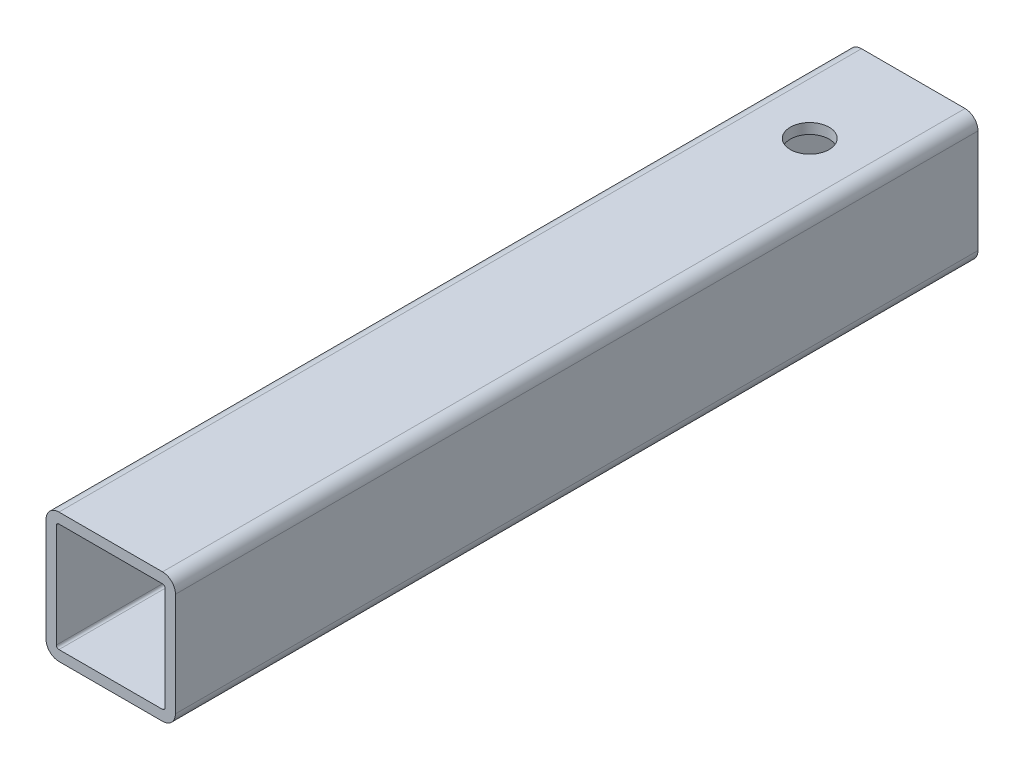
SolidWorks part; units mm, degrees
ref_plane "Front Plane" through (0, 0, 0) normal (0, 0, 1) x (1, 0, 0)
ref_plane "Top Plane" through (0, 0, 0) normal (0, 1, 0) x (1, 0, 0)
ref_plane "Right Plane" through (0, 0, 0) normal (1, 0, 0) x (0, 0, -1)
sketch "Sketch1" plane through (0, 0, 0) normal (1, 0, 0) x (0, 0, -1)
  line L0 (155, 0) -> (-155, 0)
  point P4 (0, 0)
  dimension "D1" = 310
other "Tube square TS3X3X0.3125(3)"
ref_plane "Plane1" through (0, 0, -155) normal (0, 0, 1) x (0, -1, 0)
sketch "Sketch11" plane through (0, 0, -155) normal (0, 0, 1) x (0, -1, 0)
  line L0 (-20, -21) -> (20, -21)
  line L1 (-21, -20) -> (-21, 20)
  line L2 (20, 21) -> (-20, 21)
  line L3 (21, 20) -> (21, -20)
  line L4 (-20, -25) -> (20, -25)
  line L5 (-25, -20) -> (-25, 20)
  line L6 (20, 25) -> (-20, 25)
  line L7 (25, 20) -> (25, -20)
  line L8 (-25, 0) -> (-21, 0) construction
  line L9 (-21, 0) -> (21, 0) construction
  line L10 (21, 0) -> (25, 0) construction
  line L11 (0, 25) -> (0, 21) construction
  line L12 (0, 21) -> (0, -21) construction
  line L13 (0, -21) -> (0, -25) construction
  arc A0 (25, 20) -> (20, 25) centre (20, 20) ccw
  arc A1 (20, -25) -> (25, -20) centre (20, -20) ccw
  arc A2 (-25, -20) -> (-20, -25) centre (-20, -20) ccw
  arc A3 (-20, 25) -> (-25, 20) centre (-20, 20) ccw
  arc A4 (-20, 21) -> (-21, 20) centre (-20, 20) ccw
  arc A5 (21, 20) -> (20, 21) centre (20, 20) ccw
  arc A6 (20, -21) -> (21, -20) centre (20, -20) ccw
  arc A7 (-21, -20) -> (-20, -21) centre (-20, -20) ccw
  point P6 (-25, -25)
  point P33 (-25, 25)
  point P34 (-154.2748, 59.9143)
  point P35 (25, 25)
  point P36 (25, -25)
  point P37 (0, 0)
  point P38 (0, 0)
  dimension "Thickness" = 4
  dimension "V_leg" = 50
  dimension "H_leg" = 50
sketch "Sketch12" plane through (0, 25, 0) normal (0, 1, 0) x (1, 0, 0)
  line L0 (20, -155) -> (-20, -155) construction
  line L1 (20, 155) -> (-20, 155) construction
  circle A0 centre (0, 115) radius 7.5
  point P4 (0, -155)
  dimension "D1" = 15
  dimension "D2" = 40
extrude "Cut-Extrude1" cut sketch "Sketch12" against normal through all
